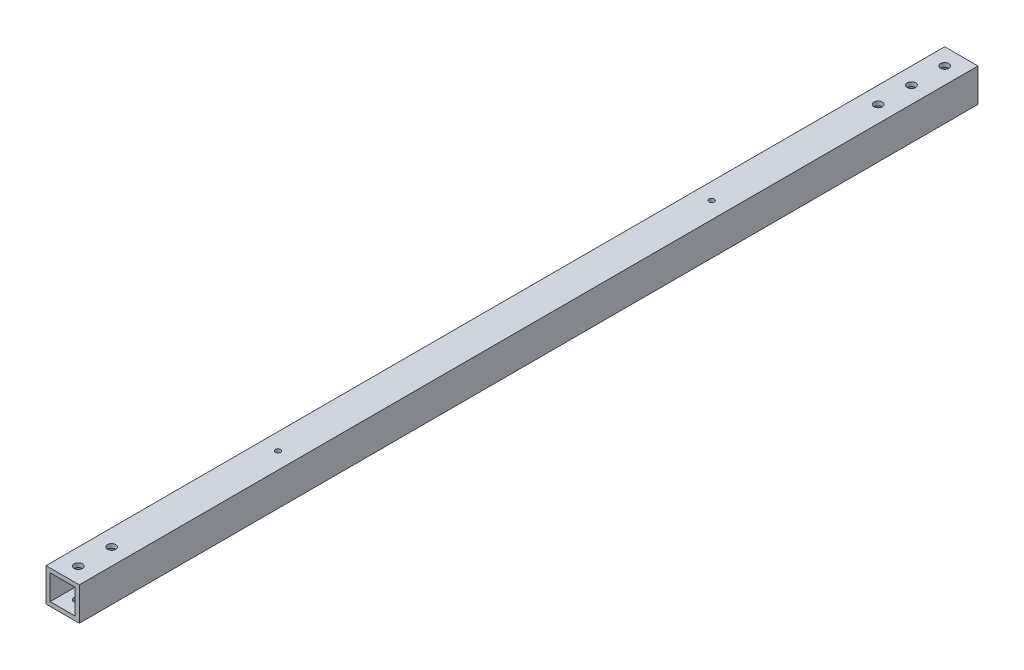
SolidWorks part; units mm, degrees
material "1060 Alloy"
ref_plane "Front Plane" through (0, 0, 0) normal (0, 0, 1) x (1, 0, 0)
ref_plane "Top Plane" through (0, 0, 0) normal (0, 1, 0) x (1, 0, 0)
ref_plane "Right Plane" through (0, 0, 0) normal (1, 0, 0) x (0, 0, -1)
sketch "Sketch1" plane through (0, 0, 0) normal (0, 0, 1) x (1, 0, 0)
  line L0 (-9.525, 9.525) -> (9.525, 9.525)
  line L2 (-12.7, 12.7) -> (12.7, 12.7)
  line L3 (-12.7, 12.7) -> (-12.7, -12.7)
  line L4 (-12.7, -12.7) -> (12.7, -12.7)
  line L5 (12.7, 12.7) -> (12.7, -12.7)
  line L10 (9.525, 9.525) -> (9.525, -9.525)
  line L11 (-9.525, -9.525) -> (9.525, -9.525)
  line L12 (-9.525, 9.525) -> (-9.525, -9.525)
  point P12 (0, 12.7)
  point P14 (12.7, 0)
  dimension "Wall Thickness" = 3.175
  dimension "Outside Width" = 25.4
  dimension "Outside Height" = 25.4
  dimension "Inside Height" = 19.05
  dimension "Inside Width" = 19.05
sketch "Sketch2" plane through (0, 0, 0) normal (1, 0, 0) x (0, 0, -1)
  line L0 (342.9, 0) -> (-342.9, 0)
  point P4 (0, 0)
  point P7 (-342.9, 0)
  point P10 (342.9, 0)
  dimension "Length" = 685.8
sketch "Sketch3" plane through (0, 0, 0) normal (0, 0, 1) x (1, 0, 0)
  line L21 (12.7, 12.7) -> (-12.7, 12.7)
  line L22 (12.7, -12.7) -> (12.7, 12.7)
  line L23 (-12.7, -12.7) -> (12.7, -12.7)
  line L24 (-12.7, 12.7) -> (-12.7, -12.7)
  line L25 (12.7, 12.7) -> (-12.7, 12.7)
  line L26 (12.7, -12.7) -> (12.7, 12.7)
  line L27 (-12.7, -12.7) -> (12.7, -12.7)
  line L28 (-12.7, 12.7) -> (-12.7, -12.7)
  line L29 (9.525, 9.525) -> (-9.525, 9.525)
  line L30 (9.525, -9.525) -> (9.525, 9.525)
  line L31 (-9.525, -9.525) -> (9.525, -9.525)
  line L32 (-9.525, 9.525) -> (-9.525, -9.525)
  line L33 (9.525, 9.525) -> (-9.525, 9.525)
  line L34 (9.525, -9.525) -> (9.525, 9.525)
  line L35 (-9.525, -9.525) -> (9.525, -9.525)
  line L36 (-9.525, 9.525) -> (-9.525, -9.525)
  dimension "D1" = 0
  dimension "D2" = 0
extrude "Boss-Extrude1" add sketch "Sketch3" along normal up to vertex (342.9 mm away) and the other way up to vertex (342.9 mm away) up to point (0, 0, 342.9) other way up to point (0, 0, -342.9)
sketch "Drawing Reference" plane through (0, 0, 0) normal (1, 0, 0) x (0, 0, -1)
  line L0 (-342.9, 0) -> (342.9, 0) construction
  line L1 (0, -12.7) -> (0, 12.7) construction
  line L2 (-342.9, -12.7) -> (342.9, -12.7) construction
  line L5 (-342.9, 12.7) -> (342.9, 12.7) construction
  point P7 (-324.612, 0)
  point P8 (324.612, 0)
  dimension "D1" = 18.288
sketch "Sketch4" plane through (0, 12.7, 0) normal (0, 1, 0) x (1, 0, 0)
  line L0 (0, -342.9) -> (0, -178.5118)
  line L1 (12.7, -342.9) -> (-12.7, -342.9) construction
  line L2 (0, 342.9) -> (0, 152.4)
  line L3 (12.7, 342.9) -> (-12.7, 342.9) construction
hole_wizard "5/32 (0.15625) Diameter Hole1" positions "Sketch5" profile "Sketch6" hole size "5/32" standard "ANSI Inch" end condition through all
sketch "Sketch5" plane through (0, 12.7, 0) normal (0, 1, 0) x (1, 0, 0)
  point P0 (0, 152.4)
  point P3 (0, -178.5118)
sketch "Sketch6" plane through (0, 12.7, -152.4) normal (1, 0, 0) x (0, 0, 1)
  line L0 (0, 0) -> (0, 25.4)
  line L1 (0, 25.4) -> (1.9844, 25.4)
  line L2 (1.9844, 25.4) -> (1.9844, 0)
  line L5 (1.9844, 0) -> (0, 0)
  line L11 (0, -6.35) -> (0, 107.95) construction
  dimension "Thru Hole Dia." = 3.9688
  dimension "Thru Hole Depth" = 25.4
sketch "Sketch7" plane through (0, 12.7, 0) normal (0, 1, 0) x (1, 0, 0)
  line L0 (0, 342.9) -> (0, 330.2)
  line L1 (0, 330.2) -> (0, 304.8)
  line L2 (0, 342.9) -> (0, 152.4) construction
  line L3 (0, 304.8) -> (0, 279.4)
hole_wizard "1/4 (0.25) Diameter Hole1" positions "Sketch8" profile "Sketch9" hole size "1/4" standard "ANSI Inch" end condition through all
sketch "Sketch8" plane through (0, 12.7, 0) normal (0, 1, 0) x (1, 0, 0)
  point P0 (0, 330.2)
  point P3 (0, 304.8)
  point P6 (0, 279.4)
sketch "Sketch9" plane through (0, 12.7, -330.2) normal (1, 0, 0) x (0, 0, 1)
  line L0 (0, 0) -> (0, 25.4)
  line L1 (0, 25.4) -> (3.9624, 25.4)
  line L2 (3.175, 24.4942) -> (3.175, 0)
  line L5 (3.175, 0) -> (0, 0)
  line L7 (3.9624, 25.4) -> (3.175, 24.4942)
  line L8 (-3.9624, 25.4) -> (-3.175, 24.4942) construction
  line L11 (0, -6.35) -> (0, 107.95) construction
  dimension "Thru Hole Dia." = 6.35
  dimension "Thru Hole Depth" = 25.4
  dimension "Far C'Sink Dia." = 7.9248
  dimension "Far C'Sink Angle" = 82
sketch "Sketch10" plane through (0, 12.7, 0) normal (0, 1, 0) x (1, 0, 0)
  line L0 (0, -342.9) -> (0, -330.9118)
  line L1 (0, -330.9118) -> (0, -305.5118)
  line L2 (0, -342.9) -> (0, -178.5118) construction
hole_wizard "1/4 (0.25) Diameter Hole2" positions "Sketch11" profile "Sketch12" hole size "1/4" standard "ANSI Inch" end condition through all
sketch "Sketch11" plane through (0, 12.7, 0) normal (0, 1, 0) x (1, 0, 0)
  point P0 (0, -330.9118)
  point P3 (0, -305.5118)
sketch "Sketch12" plane through (0, 12.7, 330.9118) normal (1, 0, 0) x (0, 0, 1)
  line L0 (0, 0) -> (0, 25.4)
  line L1 (0, 25.4) -> (3.9624, 25.4)
  line L2 (3.175, 24.4942) -> (3.175, 0)
  line L5 (3.175, 0) -> (0, 0)
  line L7 (3.9624, 25.4) -> (3.175, 24.4942)
  line L8 (-3.9624, 25.4) -> (-3.175, 24.4942) construction
  line L11 (0, -6.35) -> (0, 107.95) construction
  dimension "Thru Hole Dia." = 6.35
  dimension "Thru Hole Depth" = 25.4
  dimension "Far C'Sink Dia." = 7.9248
  dimension "Far C'Sink Angle" = 82
equation "\"D1@Drawing Reference\"=\"Outside Width@Sketch1\" * 0.72"
